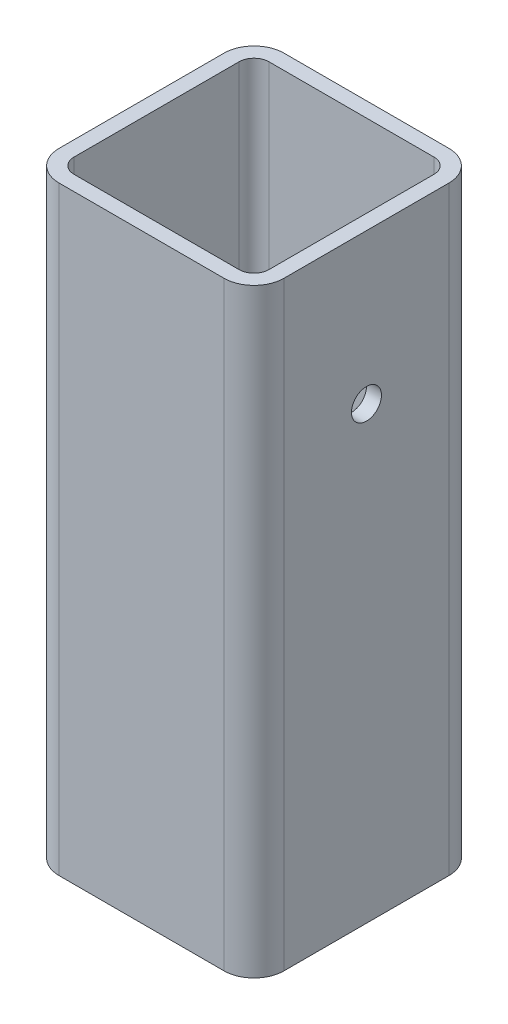
SolidWorks part; units mm, degrees
ref_plane "前视基准面" through (0, 0, 0) normal (0, 0, 1) x (1, 0, 0)
ref_plane "上视基准面" through (0, 0, 0) normal (0, 1, 0) x (1, 0, 0)
ref_plane "右视基准面" through (0, 0, 0) normal (1, 0, 0) x (0, 0, -1)
sketch "草图1" plane through (0, 0, 0) normal (0, 1, 0) x (1, 0, 0)
  line L0 (-11, -13) -> (11, -13)
  line L1 (-11, -15) -> (11, -15)
  line L2 (-15, -11) -> (-15, 11)
  line L3 (-11, 15) -> (11, 15)
  line L4 (15, -11) -> (15, 11)
  line L5 (13, -11) -> (13, 11)
  line L6 (-11, 13) -> (11, 13)
  line L7 (-13, -11) -> (-13, 11)
  arc A0 (-11, -15) -> (-15, -11) centre (-11, -11) cw
  arc A1 (11, -15) -> (15, -11) centre (11, -11) ccw
  arc A2 (11, 15) -> (15, 11) centre (11, 11) cw
  arc A3 (-15, 11) -> (-11, 15) centre (-11, 11) cw
  arc A4 (11, -13) -> (13, -11) centre (11, -11) ccw
  arc A5 (11, 13) -> (13, 11) centre (11, 11) cw
  arc A6 (-13, 11) -> (-11, 13) centre (-11, 11) cw
  arc A7 (-11, -13) -> (-13, -11) centre (-11, -11) cw
extrude "凸台-拉伸1" add sketch "草图1" along normal mid plane 80
sketch "草图2" plane through (0, 0, 0) normal (1, 0, 0) x (0, 0, -1)
  circle A0 centre (0, 20) radius 2
  point P2 (0, 0)
  dimension "D1" = 4
  dimension "D2" = 20
extrude "切除-拉伸1" cut sketch "草图2" against normal through all both and the other way through all
